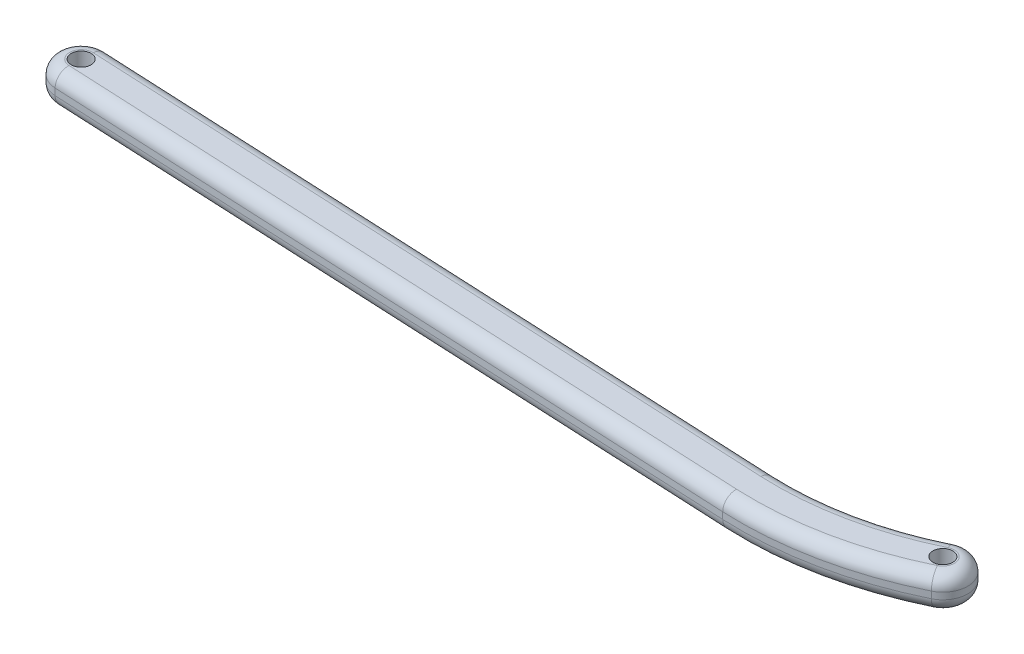
SolidWorks part; units mm, degrees
material "ABS PC"
ref_plane "Alzado" through (0, 0, 0) normal (1, 0, 0) x (0, 1, 0)
ref_plane "Planta" through (0, 0, 0) normal (0, 0, 1) x (0, 1, 0)
ref_plane "Vista lateral" through (0, 0, 0) normal (0, 1, 0) x (-1, 0, 0)
sketch "Croquis1" plane through (0, 0, 0) normal (0, 1, 0) x (-1, 0, 0)
  line L0 (0, 0) -> (260, 0) construction
  line L1 (48.5638, 10.0081) -> (260, 0) construction
  line L2 (48.9184, 17.4997) -> (260.3546, 7.4916)
  line L3 (48.2092, 2.5165) -> (259.6454, -7.4916)
  line L4 (260, 0) -> (48.5638, 10.0081) construction
  line L9 (130, -7.5) -> (130, 0) construction
  line L10 (0, 0) -> (43.8357, -89.8801) construction
  line L11 (43.8357, -89.8801) -> (48.5638, 10.0081) construction
  circle A0 centre (0, 0) radius 3
  circle A1 centre (260, 0) radius 3
  arc A2 (3.2877, -6.741) -> (48.2092, 2.5165) centre (43.8357, -89.8801) cw
  arc A16 (259.6454, -7.4916) -> (260.3546, 7.4916) centre (260, 0) ccw
  arc A17 (0, 0) -> (48.5638, 10.0081) centre (43.8357, -89.8801) cw construction
  arc A20 (0, 0) -> (48.5638, 10.0081) centre (43.8357, -89.8801) cw construction
  arc A25 (-3.2877, 6.741) -> (3.2877, -6.741) centre (0, 0) ccw
  arc A27 (-3.2877, 6.741) -> (48.9184, 17.4997) centre (43.8357, -89.8801) cw
  arc A28 (3.2877, -6.741) -> (48.2092, 2.5165) centre (43.8357, -89.8801) cw construction
  point P12 (189.4945, 12.5454)
  point P24 (58.428, 23.6733)
  dimension "D3" = 6
  dimension "D2" = 100
  dimension "D4" = 7.5
  dimension "D1" = 260
  dimension "D5" = 2.71
extrude "Saliente-Extruir1" add sketch "Croquis1" along normal mid plane 10
fillet "Redondeo7" radius 4 12 edges at (-154.6365, 5, 12.4956) (-267.4916, 5, -0.3546) (-153.9273, 5, -2.4876) (6.741, 5, -3.2877) (-154.6365, -5, 12.4956) (-267.4916, -5, -0.3546) (-153.9273, -5, -2.4876) (6.741, -5, -3.2877) (-22.1379, -5, 15.4074) (-25.1655, -5, 0.7161) (-22.1379, 5, 15.4074) (-25.1655, 5, 0.7161)
equation "\"L1\"=250"
equation "\"ancho\"= 15"
equation "\"esp\"= 10"
equation "\"agujeros\"= 6"
equation "\"L2\"=260"
equation "\"D1@Croquis1\"=\"L2\""
equation "\"D3@Croquis1\"=\"agujeros\""
equation "\"D1@Saliente-Extruir1\"=\"esp\""
